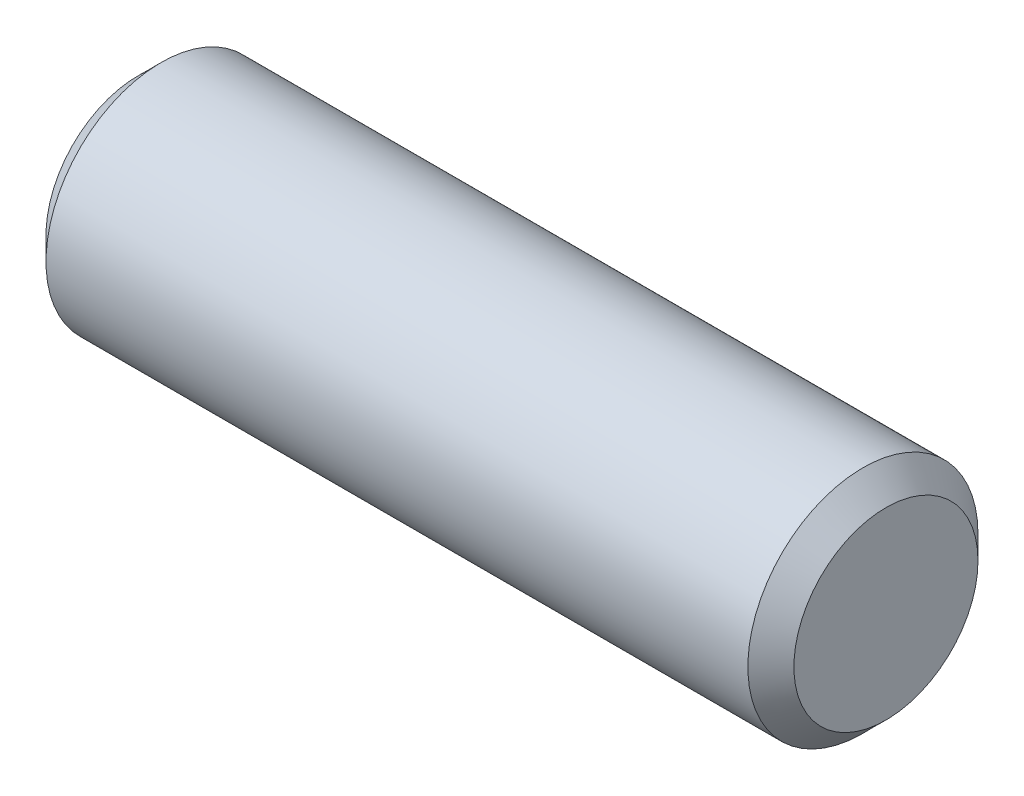
SolidWorks part; units mm, degrees
material "Plain Carbon Steel"
ref_plane "Front" through (0, 0, 0) normal (0, 0, 1) x (1, 0, 0)
ref_plane "Top" through (0, 0, 0) normal (0, 1, 0) x (1, 0, 0)
ref_plane "Right" through (0, 0, 0) normal (1, 0, 0) x (0, 0, -1)
sketch "Sketch1" plane through (0, 0, 0) normal (0, 0, 1) x (1, 0, 0)
  line L0 (-10.3187, 0) -> (10.3187, 0) construction
  line L1 (10.3188, 3.175) -> (10.3188, -3.175) construction
  line L2 (-10.3188, 3.175) -> (-10.3188, -3.175) construction
  dimension "Length" = 20.6375
  dimension "Diameter" = 6.35
sketch "Sketch2" plane through (0, 0, 0) normal (1, 0, 0) x (0, 0, -1)
  circle A0 centre (0, 0) radius 3.175
extrude "Extrude1" add sketch "Sketch2" against normal up to vertex (10.3187 mm away) and the other way up to vertex (10.3187 mm away) up to point (-10.3188, 3.175, 0) other way up to point (10.3188, 3.175, 0)
chamfer "Chamfer1" distance 0.635 angle 45 2 edges at (10.3188, 0, -3.175) (-10.3188, 0, -3.175)
equation "\"D1@Chamfer1\" = \"Diameter@Sketch1\"*.1"
